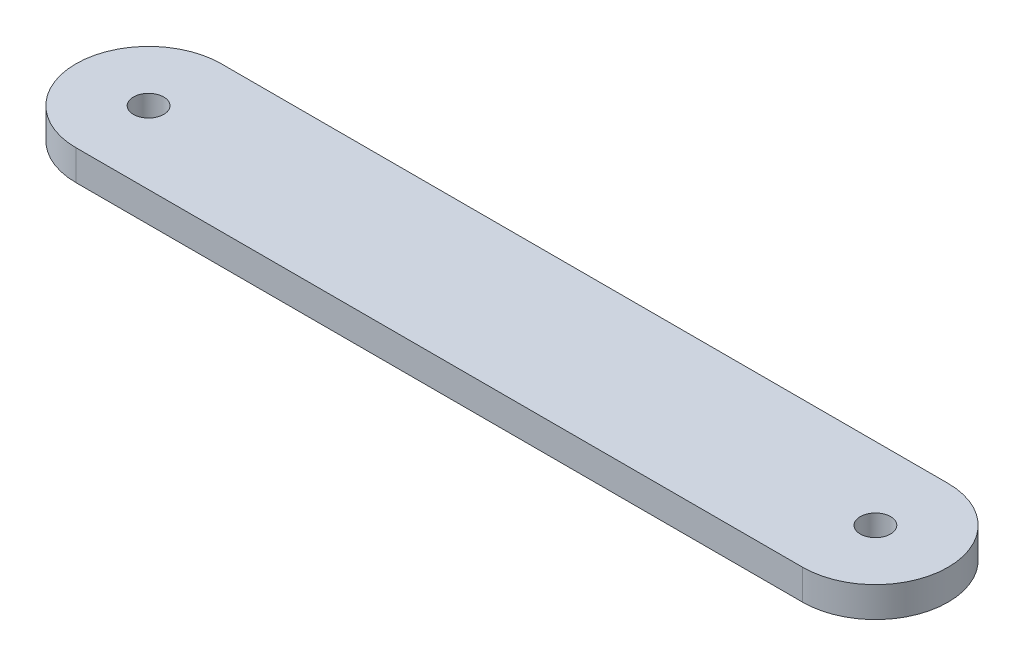
SolidWorks part; units mm, degrees
ref_plane "Спереди" through (0, 0, 0) normal (0, 0, 1) x (1, 0, 0)
ref_plane "Сверху" through (0, 0, 0) normal (0, 1, 0) x (1, 0, 0)
ref_plane "Справа" through (0, 0, 0) normal (1, 0, 0) x (0, 0, -1)
sketch "Эскиз1" plane through (0, 0, 0) normal (0, 1, 0) x (1, 0, 0)
  line L0 (0, 10.1778) -> (120, 10.1778)
  line L1 (0, -13.8222) -> (120, -13.8222)
  circle A0 centre (0, -1.8222) radius 2.5
  arc A1 (0, 10.1778) -> (0, -13.8222) centre (0, -1.8222) ccw
  circle A2 centre (120, -1.8222) radius 2.5
  arc A3 (120, -13.8222) -> (120, 10.1778) centre (120, -1.8222) ccw
  dimension "D1" = 120
extrude "Вытянуть1" add sketch "Эскиз1" along normal blind 5
